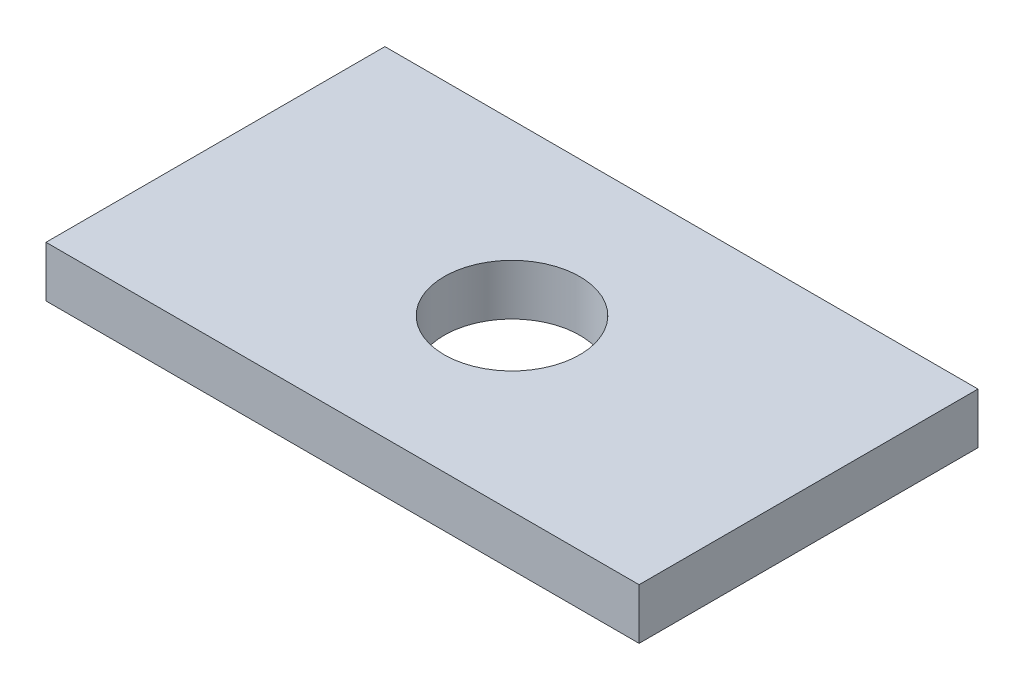
SolidWorks part; units mm, degrees
ref_plane "Front Plane" through (0, 0, 0) normal (0, 0, 1) x (1, 0, 0)
ref_plane "Top Plane" through (0, 0, 0) normal (0, 1, 0) x (1, 0, 0)
ref_plane "Right Plane" through (0, 0, 0) normal (1, 0, 0) x (0, 0, -1)
sketch "Sketch1" plane through (0, 0, 0) normal (0, 0, 1) x (1, 0, 0)
  line L1 (-35, -3) -> (35, -3)
  line L2 (-35, -3) -> (-35, 3)
  line L3 (-35, 3) -> (35, 3)
  line L4 (35, -3) -> (35, 3)
  line L5 (-35, -3) -> (35, 3) construction
  line L6 (-35, 3) -> (35, -3) construction
  point P0 (0, 0)
  dimension "D1" = 6
  dimension "D2" = 70
extrude "Boss-Extrude1" add sketch "Sketch1" along normal blind 40
sketch "Sketch2" plane through (0, 3, 0) normal (0, 1, 0) x (1, 0, 0)
  line L0 (-35, 0) -> (35, -40) construction
  line L1 (-35, -40) -> (35, 0) construction
  circle A0 centre (0, -20) radius 8
  point P11 (0, -20)
  dimension "D1" = 16
extrude "Cut-Extrude1" cut sketch "Sketch2" against normal through all
ref_plane "Plane1" through (0, 0, 20) normal (0, 0, 1) x (1, 0, 0)
ref_plane "Plane2" through (-10, 0, 10) normal (0.7071, 0, -0.7071) x (-0.7071, 0, -0.7071)
ref_plane "Plane3" through (10, 0, 10) normal (0.7071, 0, 0.7071) x (0.7071, 0, -0.7071)
